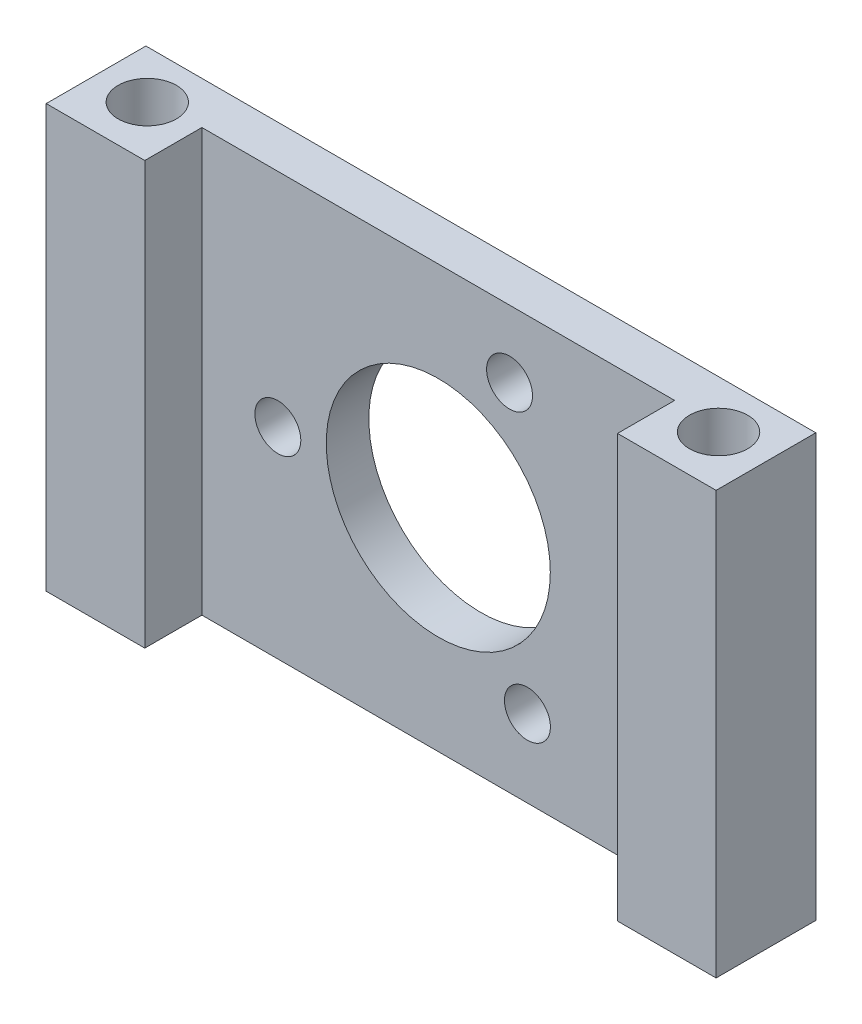
SolidWorks part; units mm, degrees
ref_plane "Front Plane" through (0, 0, 0) normal (0, 0, 1) x (1, 0, 0)
ref_plane "Top Plane" through (0, 0, 0) normal (0, 1, 0) x (1, 0, 0)
ref_plane "Right Plane" through (0, 0, 0) normal (1, 0, 0) x (0, 0, -1)
sketch "Sketch1" plane through (0, 0, 0) normal (0, 0, 1) x (1, 0, 0)
  line L1 (-29.9, 18.85) -> (29.9, 18.85)
  line L2 (-29.9, 18.85) -> (-29.9, -18.85)
  line L3 (-29.9, -18.85) -> (29.9, -18.85)
  line L4 (29.9, 18.85) -> (29.9, -18.85)
  line L5 (-29.9, 18.85) -> (29.9, -18.85) construction
  line L6 (-29.9, -18.85) -> (29.9, 18.85) construction
  point P0 (0, 0)
  dimension "D1" = 37.7
  dimension "D2" = 59.8
extrude "Boss-Extrude1" add sketch "Sketch1" along normal blind 8.9
sketch "Sketch2" plane through (0, 0, 8.9) normal (0, 0, 1) x (1, 0, 0)
  line L0 (29.9, 18.85) -> (-29.9, 18.85) construction
  line L1 (-21.1, 18.85) -> (21.1, 18.85)
  line L2 (-21.1, 18.85) -> (-21.1, -18.85)
  line L3 (-21.1, -18.85) -> (21.1, -18.85)
  line L4 (21.1, 18.85) -> (21.1, -18.85)
  line L5 (-29.9, -18.85) -> (29.9, -18.85) construction
  line L6 (-29.9, 18.85) -> (-29.9, -18.85) construction
  line L7 (29.9, -18.85) -> (29.9, 18.85) construction
  dimension "D1" = 8.8
  dimension "D2" = 8.8
extrude "Cut-Extrude1" cut sketch "Sketch2" against normal blind 5.1
sketch "Sketch3" plane through (0, 18.85, 0) normal (0, 1, 0) x (1, 0, 0)
  line L0 (29.9, -8.9) -> (29.9, 0) construction
  line L1 (0, 0) -> (0, 5.3293) construction
  circle A0 centre (25.5, -4.2787) radius 2.6
  circle A1 centre (-25.5, -4.2787) radius 2.6
  dimension "D1" = 4.4
  dimension "D2" = 5.2
extrude "Cut-Extrude2" cut sketch "Sketch3" against normal through all
sketch "Sketch4" plane through (0, 0, 3.8) normal (0, 0, 1) x (1, 0, 0)
  line L2 (0, 0) -> (0, 14.6379) construction
  circle A0 centre (0, 0) radius 10
  circle A6 centre (7.9578, -11.9414) radius 2.05
  circle A8 centre (-14.3204, -0.9209) radius 2.05
  circle A10 centre (6.3627, 12.8623) radius 2.05
  point P2 (0, 0)
  point P4 (0, 0)
  point P5 (0, 0)
  dimension "D1" = 20
  dimension "D2" = 4.1
  dimension "D3" = 4.1
  dimension "D4" = 4.1
extrude "Cut-Extrude3" cut sketch "Sketch4" against normal through all
